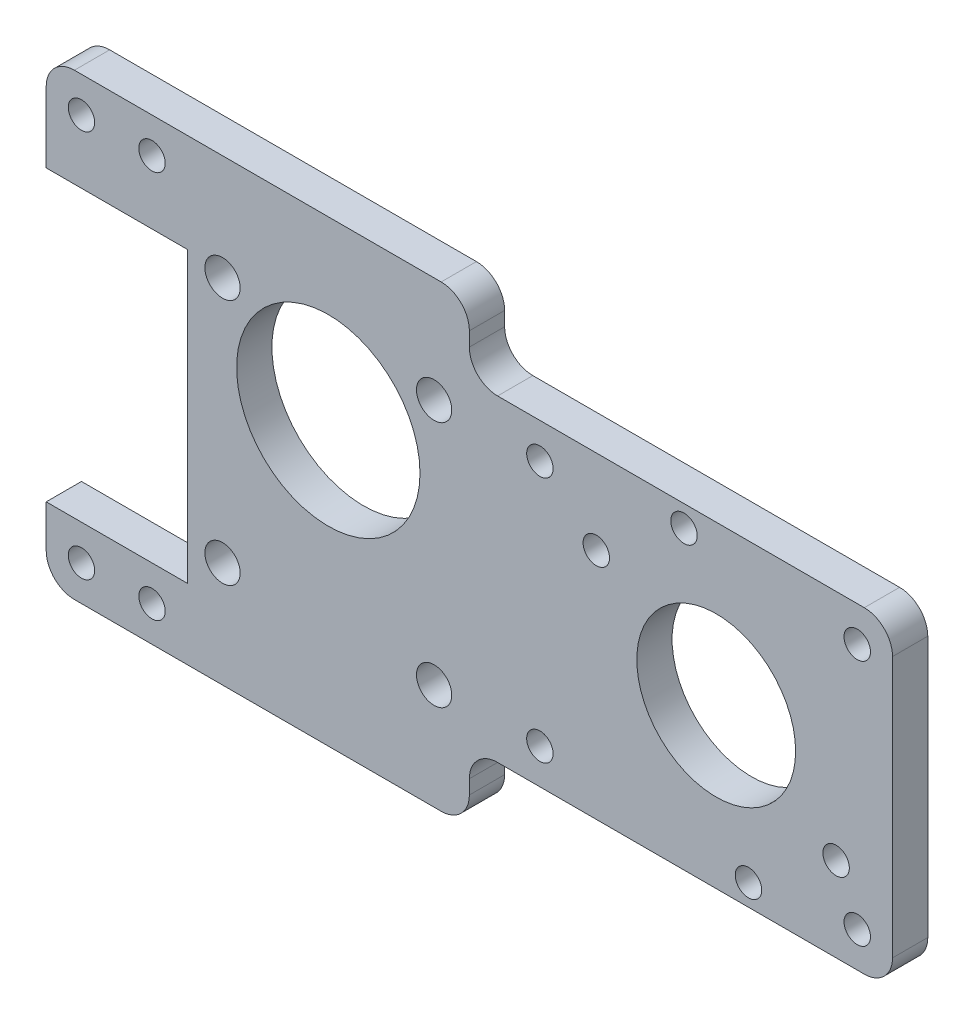
SolidWorks part; units mm, degrees
material "6061-T6 (SS)"
ref_plane "Front Plane" through (0, 0, 0) normal (0, 0, 1) x (1, 0, 0)
ref_plane "Top Plane" through (0, 0, 0) normal (0, 1, 0) x (1, 0, 0)
ref_plane "Right Plane" through (0, 0, 0) normal (1, 0, 0) x (0, 0, -1)
sketch "Sketch1" plane through (0, 0, 0) normal (0, 0, 1) x (1, 0, 0)
  line L1 (-63.5, 28.575) -> (63.5, 28.575)
  line L2 (-63.5, 28.575) -> (-63.5, -28.575)
  line L3 (-63.5, -28.575) -> (63.5, -28.575)
  line L4 (63.5, 28.575) -> (63.5, -28.575)
  line L5 (-63.5, 28.575) -> (63.5, -28.575) construction
  line L6 (-63.5, -28.575) -> (63.5, 28.575) construction
  circle A0 centre (31.75, 0) radius 14.3002
  circle A1 centre (31.75, 0) radius 25.4 construction
  circle A2 centre (37.5551, -24.7277) radius 2.3812
  circle A3 centre (18.3697, -21.59) radius 2.3813
  circle A4 centre (7.0223, -5.8051) radius 2.3813
  circle A5 centre (10.16, 13.3803) radius 2.3813
  circle A6 centre (25.9449, 24.7277) radius 2.3813
  circle A7 centre (45.1303, 21.59) radius 2.3812
  circle A8 centre (56.4777, 5.8051) radius 2.3812
  circle A9 centre (53.34, -13.3803) radius 2.3812
  point P0 (0, 0)
  point P27 (31.75, 0)
  dimension "D3" = 28.6004
  dimension "D5" = 50.8
  dimension "D8" = 4.7625
  dimension "D1" = 127
  dimension "D2" = 57.15
  dimension "D4" = 31.75
  dimension "D7" = 21.59
  dimension "D6" = 8
extrude "Boss-Extrude1" add sketch "Sketch1" along normal blind 6.35 contours A8 L4 L1 L2 L3 A9 A7 A6 A5 A4 A3 A2 A0 | L4 A8 | A3 | A4 | A7
sketch "Sketch2" plane through (0, 0, 6.35) normal (0, 0, 1) x (1, 0, 0)
  line L0 (-63.5, 28.575) -> (63.5, 28.575) construction
  line L1 (63.5, 28.575) -> (63.5, -28.575) construction
  line L2 (-63.5, -28.575) -> (63.5, -28.575) construction
  circle A0 centre (57.15, 22.225) radius 2.3812
  circle A1 centre (57.15, -22.225) radius 2.3812
  circle A2 centre (0, 22.225) radius 2.3813
  circle A3 centre (0, -22.225) radius 2.3813
  dimension "D1" = 4.7625
  dimension "D4" = 4.7625
  dimension "D7" = 4.7625
  dimension "D8" = 4.7625
  dimension "D2" = 6.35
  dimension "D3" = 6.35
  dimension "D5" = 6.35
  dimension "D6" = 6.35
  dimension "D9" = 57.15
  dimension "D10" = 57.15
  dimension "D11" = 6.35
  dimension "D12" = 6.35
extrude "Cut-Extrude1" cut sketch "Sketch2" against normal through all
fillet "Fillet1" radius 5.08 2 edges at (63.5, -28.575, 3.175) (63.5, 28.575, 3.175)
sketch "Sketch3" plane through (0, 0, 6.35) normal (0, 0, 1) x (1, 0, 0)
  line L0 (-63.5, 28.575) -> (-63.5, -28.575) construction
  line L1 (-63.5, 28.575) -> (58.42, 28.575) construction
  line L2 (-63.5, 0) -> (63.5, 0) construction
  line L3 (63.5, 23.495) -> (63.5, -23.495) construction
  circle A0 centre (-57.15, 22.225) radius 3.175
  circle A1 centre (-19.05, 22.225) radius 3.175
  circle A2 centre (-19.05, -22.225) radius 3.175
  circle A3 centre (-57.15, -22.225) radius 3.175
  dimension "D3" = 6.35
  dimension "D4" = 6.35
  dimension "D1" = 6.35
  dimension "D2" = 6.35
  dimension "D5" = 38.1
extrude "Cut-Extrude2" cut sketch "Sketch3" against normal through all
sketch "Sketch4" plane through (0, 0, 6.35) normal (0, 0, 1) x (1, 0, 0)
  line L0 (-63.5, 28.575) -> (58.42, 28.575) construction
  line L1 (-63.5, 28.575) -> (-63.5, -28.575) construction
  circle A0 centre (-38.1, 9.525) radius 16.51
  dimension "D1" = 33.02
  dimension "D2" = 19.05
  dimension "D3" = 25.4
extrude "Cut-Extrude3" cut sketch "Sketch4" against normal blind 7.62
sketch "Sketch5" plane through (0, 0, 6.35) normal (0, 0, 1) x (1, 0, 0)
  line L0 (-63.5, -28.575) -> (58.42, -28.575) construction
  line L1 (-12.7, -28.575) -> (-88.9, -28.575)
  line L2 (-12.7, -28.575) -> (-12.7, -41.275)
  line L3 (-12.7, -41.275) -> (-88.9, -41.275)
  line L4 (-88.9, -28.575) -> (-88.9, -41.275)
  line L5 (-63.5, 28.575) -> (-63.5, -28.575) construction
  line L6 (-63.5, 28.575) -> (58.42, 28.575) construction
  line L7 (-12.7, 28.575) -> (-88.9, 28.575)
  line L8 (-12.7, 28.575) -> (-12.7, 41.275)
  line L9 (-12.7, 41.275) -> (-88.9, 41.275)
  line L10 (-88.9, 28.575) -> (-88.9, 41.275)
  dimension "D1" = 50.8
  dimension "D2" = 12.7
  dimension "D3" = 25.4
  dimension "D4" = 12.7
  dimension "D5" = 25.4
  dimension "D6" = 50.8
extrude "Boss-Extrude2" add sketch "Sketch5" against normal blind 6.35
fillet "Fillet2" radius 5.08 4 edges at (-12.7, -41.275, 3.175) (-12.7, -28.575, 3.175) (-12.7, 41.275, 3.175) (-12.7, 28.575, 3.175)
sketch "Sketch6" plane through (0, 0, 6.35) normal (0, 0, 1) x (1, 0, 0)
  line L0 (-88.9, 41.275) -> (-88.9, 28.575) construction
  line L1 (-63.5, 28.575) -> (-88.9, 28.575)
  line L2 (-63.5, 28.575) -> (-63.5, 23.495)
  line L3 (-63.5, 23.495) -> (-88.9, 23.495)
  line L4 (-88.9, 28.575) -> (-88.9, 23.495)
  line L5 (-63.5, -28.575) -> (-88.9, -28.575) construction
  dimension "D1" = 52.07
extrude "Boss-Extrude3" add sketch "Sketch6" against normal blind 6.35
fillet "Fillet3" radius 5.08 2 edges at (-88.9, 41.275, 3.175) (-88.9, -41.275, 3.175)
sketch "Sketch7" plane through (0, 0, 6.35) normal (0, 0, 1) x (1, 0, 0)
  line L0 (-88.9, -28.575) -> (-88.9, -36.195) construction
  line L1 (-88.9, 36.195) -> (-88.9, 23.495) construction
  line L2 (-83.82, -41.275) -> (-17.78, -41.275) construction
  line L3 (-17.78, 41.275) -> (-83.82, 41.275) construction
  line L4 (-17.78, 41.275) -> (-83.82, 41.275) construction
  circle A0 centre (-82.55, 34.925) radius 2.3813
  circle A1 centre (-82.55, -34.925) radius 2.3813
  circle A2 centre (-69.85, 34.925) radius 2.3813
  circle A3 centre (-69.85, -34.925) radius 2.3813
  dimension "D1" = 4.7625
  dimension "D2" = 4.7625
  dimension "D7" = 4.7625
  dimension "D8" = 4.7625
  dimension "D3" = 6.35
  dimension "D4" = 6.35
  dimension "D5" = 6.35
  dimension "D6" = 6.35
  dimension "D9" = 6.35
  dimension "D10" = 6.35
  dimension "D11" = 12.7
  dimension "D12" = 12.7
extrude "Cut-Extrude4" cut sketch "Sketch7" against normal blind 6.35
